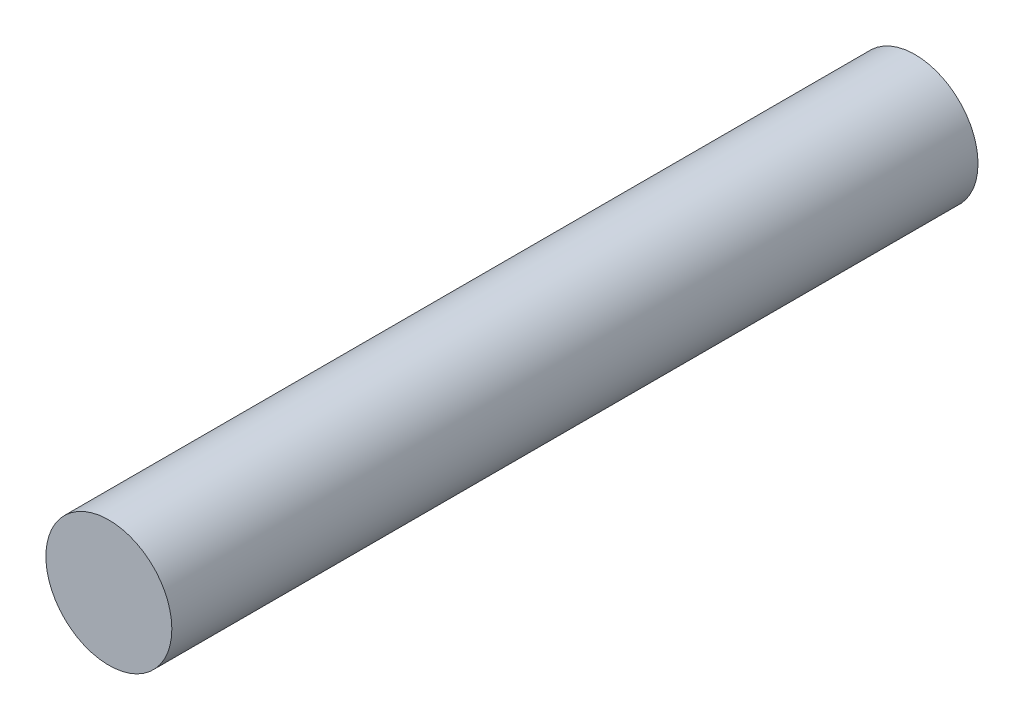
SolidWorks part; units mm, degrees
ref_plane "Front Plane" through (0, 0, 0) normal (0, 0, 1) x (1, 0, 0)
ref_plane "Top Plane" through (0, 0, 0) normal (0, 1, 0) x (1, 0, 0)
ref_plane "Right Plane" through (0, 0, 0) normal (1, 0, 0) x (0, 0, -1)
sketch "Sketch1" plane through (0, 0, 0) normal (0, 0, 1) x (1, 0, 0)
  line L0 (0, 0) -> (0, 48.5349) construction
  line L1 (-20.0575, 0) -> (21.1297, 0) construction
  circle A0 centre (0, 0) radius 15.875
  dimension "D1" = 31.75
extrude "Extrude1" add sketch "Sketch1" against normal mid plane 203.2
